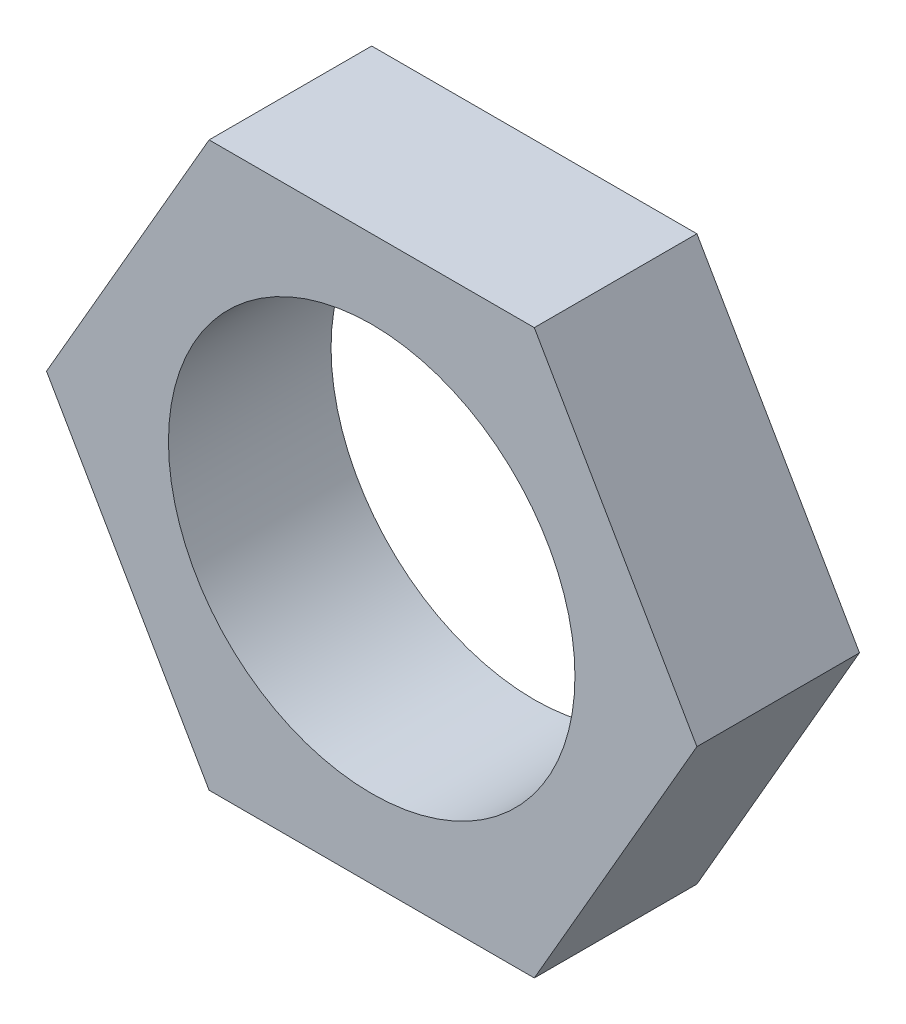
SolidWorks part; units mm, degrees
ref_plane "Front Plane" through (0, 0, 0) normal (0, 0, 1) x (1, 0, 0)
ref_plane "Top Plane" through (0, 0, 0) normal (0, 1, 0) x (1, 0, 0)
ref_plane "Right Plane" through (0, 0, 0) normal (1, 0, 0) x (0, 0, -1)
sketch "Sketch1" plane through (0, 0, 0) normal (0, 0, 1) x (1, 0, 0)
  line L0 (2.54, 4.3994) -> (-2.54, 4.3994)
  line L1 (-2.54, 4.3994) -> (-5.08, 0)
  line L2 (-5.08, 0) -> (-2.54, -4.3994)
  line L3 (-2.54, -4.3994) -> (2.54, -4.3994)
  line L4 (2.54, -4.3994) -> (5.08, 0)
  line L5 (5.08, 0) -> (2.54, 4.3994)
  circle A0 centre (0, 0) radius 3.175
  circle A1 centre (0, 0) radius 5.08
  dimension "D1" = 6.35
  dimension "D2" = 0
  dimension "D3" = 10.16
extrude "Boss-Extrude1" add sketch "Sketch1" along normal blind 2.54 contours L4 L5 L0 L1 L2 L3 A0
